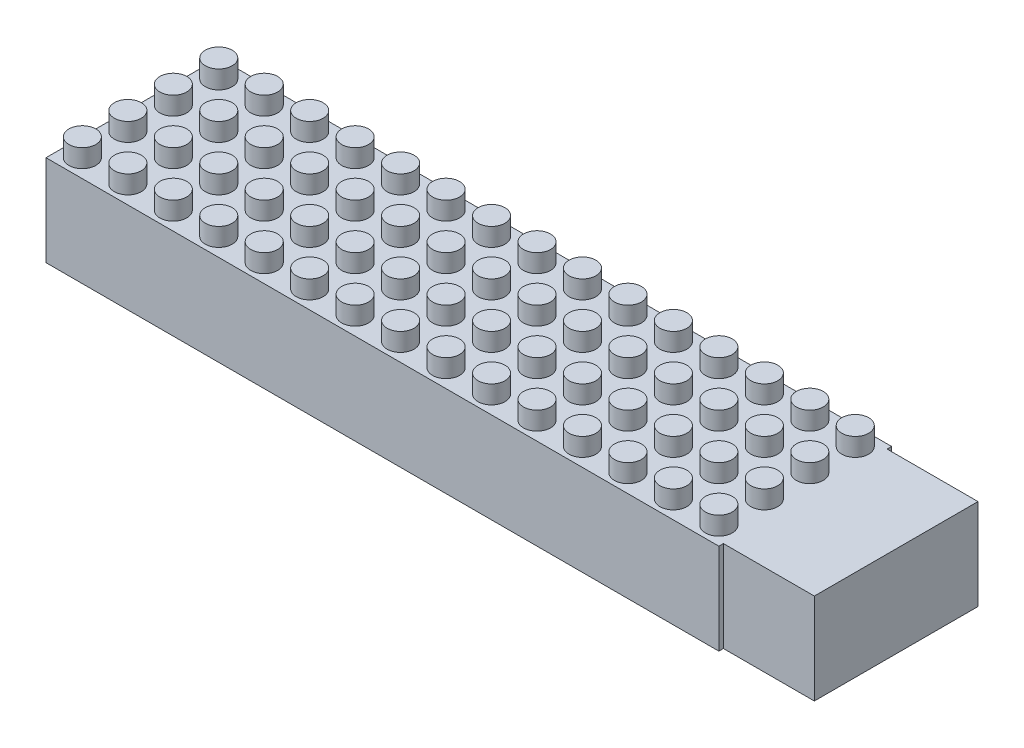
SolidWorks part; units mm, degrees
ref_plane "前视基准面" through (0, 0, 0) normal (0, 0, 1) x (1, 0, 0)
ref_plane "上视基准面" through (0, 0, 0) normal (0, 1, 0) x (1, 0, 0)
ref_plane "右视基准面" through (0, 0, 0) normal (1, 0, 0) x (0, 0, -1)
other "Configuration Table"
sketch "草图1" plane through (0, 0, 0) normal (0, 1, 0) x (1, 0, 0)
  line L1 (-370, 95) -> (370, 95)
  line L2 (-370, 95) -> (-370, -95)
  line L3 (-370, -95) -> (370, -95)
  line L4 (370, 95) -> (370, -95)
  line L5 (-370, 95) -> (370, -95) construction
  line L6 (-370, -95) -> (370, 95) construction
  point P0 (0, 0)
  dimension "D1" = 190
  dimension "D2" = 740
extrude "凸台-拉伸1" add sketch "草图1" along normal blind 100
ref_plane "基准面1" through (0, 100, 0) normal (0, 1, 0) x (1, 0, 0)
sketch "草图2" plane through (0, 100, 0) normal (0, 1, 0) x (1, 0, 0)
  line L0 (370, -95) -> (370, 95) construction
  line L1 (-370, -95) -> (370, -95) construction
  circle A0 centre (350, -75) radius 14.8124
  circle A1 centre (300, -75) radius 14.8124
  circle A2 centre (250, -75) radius 14.8124
  circle A3 centre (200, -75) radius 14.8124
  circle A4 centre (150, -75) radius 14.8124
  circle A5 centre (100, -75) radius 14.8124
  circle A6 centre (50, -75) radius 14.8124
  circle A7 centre (0, -75) radius 14.8124
  circle A8 centre (-50, -75) radius 14.8124
  circle A9 centre (-100, -75) radius 14.8124
  circle A10 centre (-150, -75) radius 14.8124
  circle A11 centre (-200, -75) radius 14.8124
  circle A12 centre (-250, -75) radius 14.8124
  circle A13 centre (-300, -75) radius 14.8124
  circle A14 centre (-350, -75) radius 14.8124
  circle A15 centre (300, -25) radius 14.8124
  circle A16 centre (250, -25) radius 14.8124
  circle A17 centre (200, -25) radius 14.8124
  circle A18 centre (150, -25) radius 14.8124
  circle A19 centre (100, -25) radius 14.8124
  circle A20 centre (50, -25) radius 14.8124
  circle A21 centre (0, -25) radius 14.8124
  circle A22 centre (-50, -25) radius 14.8124
  circle A23 centre (-100, -25) radius 14.8124
  circle A24 centre (-150, -25) radius 14.8124
  circle A25 centre (-200, -25) radius 14.8124
  circle A26 centre (-250, -25) radius 14.8124
  circle A27 centre (-300, -25) radius 14.8124
  circle A28 centre (-350, -25) radius 14.8124
  circle A29 centre (300, 25) radius 14.8124
  circle A30 centre (250, 25) radius 14.8124
  circle A31 centre (200, 25) radius 14.8124
  circle A32 centre (150, 25) radius 14.8124
  circle A33 centre (100, 25) radius 14.8124
  circle A34 centre (50, 25) radius 14.8124
  circle A35 centre (0, 25) radius 14.8124
  circle A36 centre (-50, 25) radius 14.8124
  circle A37 centre (-100, 25) radius 14.8124
  circle A38 centre (-150, 25) radius 14.8124
  circle A39 centre (-200, 25) radius 14.8124
  circle A40 centre (-250, 25) radius 14.8124
  circle A41 centre (-300, 25) radius 14.8124
  circle A42 centre (-350, 25) radius 14.8124
  circle A43 centre (300, 75) radius 14.8124
  circle A44 centre (250, 75) radius 14.8124
  circle A45 centre (200, 75) radius 14.8124
  circle A46 centre (150, 75) radius 14.8124
  circle A47 centre (100, 75) radius 14.8124
  circle A48 centre (50, 75) radius 14.8124
  circle A49 centre (0, 75) radius 14.8124
  circle A50 centre (-50, 75) radius 14.8124
  circle A51 centre (-100, 75) radius 14.8124
  circle A52 centre (-150, 75) radius 14.8124
  circle A53 centre (-200, 75) radius 14.8124
  circle A54 centre (-250, 75) radius 14.8124
  circle A55 centre (-300, 75) radius 14.8124
  circle A56 centre (-350, 75) radius 14.8124
  circle A57 centre (350, -25) radius 14.8124
  circle A58 centre (350, 25) radius 14.8124
  circle A59 centre (350, 75) radius 14.8124
  dimension "D1" = 20
  dimension "D2" = 20
  dimension "D3" = 15
  dimension "D4" = 4
extrude "凸台-拉伸2" add sketch "草图2" along normal blind 20
ref_plane "基准面2" through (370, 0, 0) normal (1, 0, 0) x (0, 0, -1)
sketch "草图3" plane through (370, 0, 0) normal (1, 0, 0) x (0, 0, -1)
  line L0 (-95, 50) -> (95, 50) construction
  line L1 (0, 100) -> (0, 0) construction
  line L3 (-90, 100) -> (90, 100)
  line L4 (-95, 0) -> (95, 0)
  line L5 (95, 0) -> (95, 100)
  line L6 (95, 100) -> (-95, 100)
  line L7 (-95, 100) -> (-95, 0)
  line L8 (-95, 0) -> (95, 0) construction
  line L9 (95, 0) -> (95, 100) construction
  line L10 (95, 100) -> (-95, 100) construction
  line L11 (-95, 100) -> (-95, 0) construction
  line L12 (-90, 100) -> (-90, 0)
  line L13 (-90, 0) -> (90, 0)
  line L14 (90, 100) -> (90, 0)
  line L15 (-90, 100) -> (90, 0) construction
  line L16 (-90, 0) -> (90, 100) construction
  point P9 (0, 50)
  dimension "D2" = 100
  dimension "D3" = 180
  dimension "D1" = 0
extrude "凸台-拉伸3" add sketch "草图3" along normal blind 100
